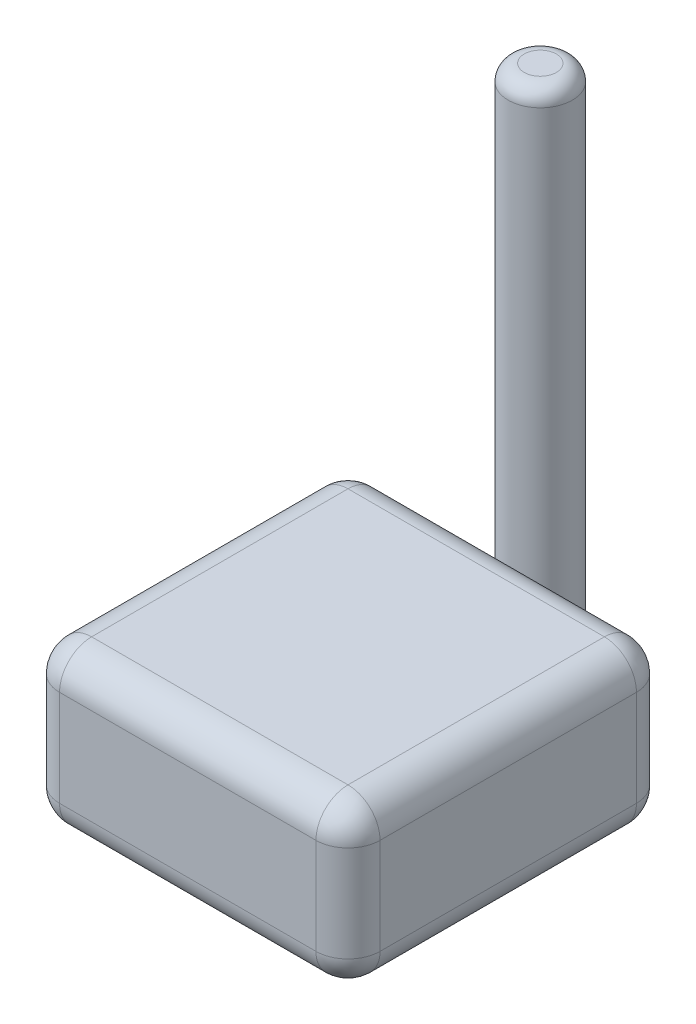
SolidWorks part; units mm, degrees
material "Polycarbonate (PC) - Unfilled"
ref_plane "Front Plane" through (0, 0, 0) normal (0, 0, 1) x (1, 0, 0)
ref_plane "Top Plane" through (0, 0, 0) normal (0, 1, 0) x (1, 0, 0)
ref_plane "Right Plane" through (0, 0, 0) normal (1, 0, 0) x (0, 0, -1)
sketch "Sketch2" plane through (0, 0, 0) normal (0, 0, 1) x (1, 0, 0)
  line L1 (-61.4264, 10.4043) -> (-41.4264, 10.4043)
  line L2 (-61.4264, 10.4043) -> (-61.4264, 20.4043)
  line L3 (-61.4264, 20.4043) -> (-41.4264, 20.4043)
  line L4 (-41.4264, 10.4043) -> (-41.4264, 20.4043)
  line L5 (-61.4264, 10.4043) -> (-41.4264, 20.4043) construction
  line L6 (-61.4264, 20.4043) -> (-41.4264, 10.4043) construction
  point P0 (-51.4264, 15.4043)
  dimension "D1" = 10
  dimension "D2" = 20
extrude "Boss-Extrude1" add sketch "Sketch2" along normal mid plane 20
fillet "Fillet1" radius 2 12 edges at (-51.4264, 10.4043, -10) (-61.4264, 15.4043, -10) (-61.4264, 10.4043, 0) (-61.4264, 15.4043, 10) (-41.4264, 15.4043, -10) (-41.4264, 10.4043, 0) (-51.4264, 10.4043, 10) (-41.4264, 15.4043, 10) (-51.4264, 20.4043, -10) (-61.4264, 20.4043, 0) (-51.4264, 20.4043, 10) (-41.4264, 20.4043, 0)
sketch "Sketch4" plane through (0, 20.4043, 0) normal (0, 1, 0) x (1, 0, 0)
  line L0 (-59.4264, 10) -> (-43.4264, 10) construction
  line L1 (-41.4264, 8) -> (-41.4264, -8) construction
  circle A0 centre (-51.4264, 12) radius 2
  dimension "D1" = 4
  dimension "D2" = 2
  dimension "D3" = 10
extrude "Boss-Extrude2" add sketch "Sketch4" along normal mid plane 30 from offset 10 separate body
fillet "Fillet2" radius 1 1 edges at (-53.4264, 45.4043, -12)
